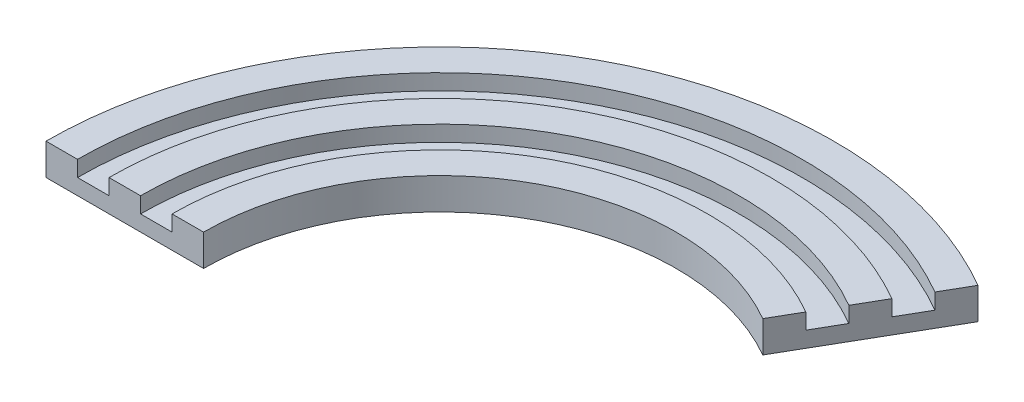
SolidWorks part; units mm, degrees
other "Published References"
other "Ground Plane"
other "Connector1"
other "Connector2"
ref_plane "Front Plane" through (0, 0, 0) normal (0, 0, 1) x (1, 0, 0)
ref_plane "Top Plane" through (0, 0, 0) normal (0, 1, 0) x (1, 0, 0)
ref_plane "Right Plane" through (0, 0, 0) normal (1, 0, 0) x (0, 0, -1)
sketch "Sketch1" plane through (0, 0, 0) normal (0, 0, 1) x (1, 0, 0)
  line L0 (0, 51.1397) -> (0, -37.9777) construction
  line L1 (25, -5) -> (-25, -5)
  line L2 (25, -5) -> (25, 5)
  line L3 (25, 5) -> (15, 5)
  line L4 (-25, -5) -> (-25, 5)
  line L5 (25, -5) -> (-25, 5) construction
  line L6 (25, 5) -> (-25, -5) construction
  line L8 (-15, 5) -> (-15, 0)
  line L9 (-15, 0) -> (-5, 0)
  line L10 (-5, 5) -> (-5, 0)
  line L12 (15, 5) -> (15, 0)
  line L13 (15, 0) -> (5, 0)
  line L14 (5, 5) -> (5, 0)
  line L15 (-15, 5) -> (-25, 5)
  line L16 (5, 5) -> (-5, 5)
  point P0 (0, 0)
  dimension "D1" = 50
  dimension "D2" = 10
  dimension "D3" = 5
  dimension "D4" = 5
  dimension "D5" = 10
sketch "Sketch2" plane through (0, 0, 0) normal (0, 1, 0) x (1, 0, 0)
  line L0 (150, 86.6025) -> (100, 0) construction
  line L1 (100, 0) -> (0, 0) construction
  arc A0 (0, 0) -> (150, 86.6025) centre (100, 0) cw
  dimension "D1" = 100
  dimension "D2" = 60
sweep "Sweep1" add profiles "Sketch1" path "Sketch2"
